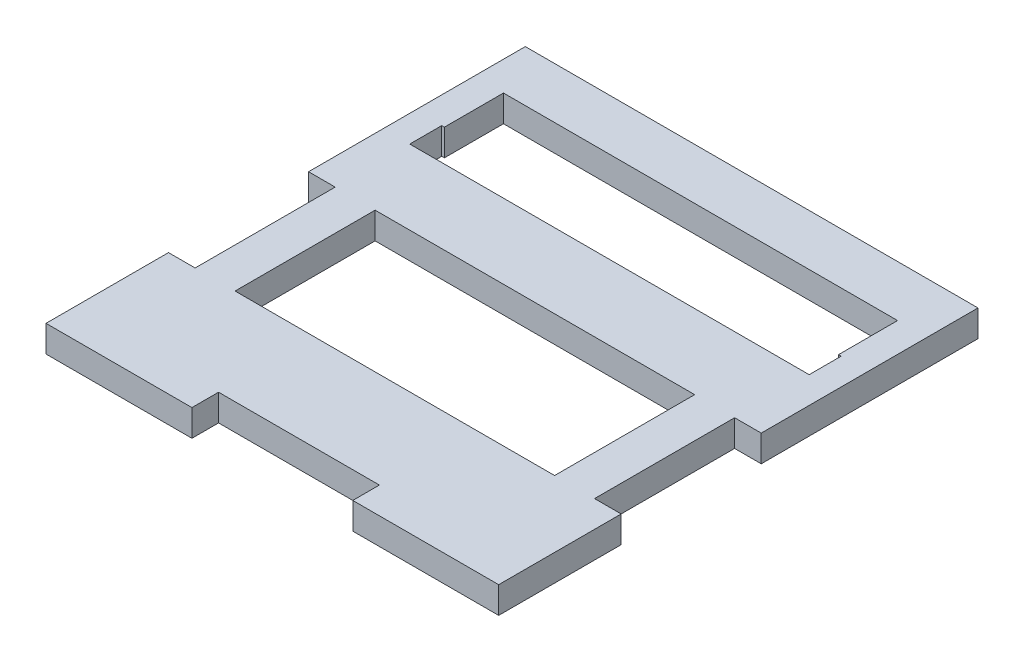
SolidWorks part; units mm, degrees
ref_plane "Front Plane" through (0, 0, 0) normal (0, 0, 1) x (1, 0, 0)
ref_plane "Top Plane" through (0, 0, 0) normal (0, 1, 0) x (1, 0, 0)
ref_plane "Right Plane" through (0, 0, 0) normal (1, 0, 0) x (0, 0, -1)
sketch "Sketch1" plane through (0, 0, 0) normal (0, 1, 0) x (1, 0, 0)
  line L1 (-42.5, -45) -> (42.5, -45)
  line L2 (-42.5, -45) -> (-42.5, 45)
  line L3 (-42.5, 45) -> (42.5, 45)
  line L4 (42.5, -45) -> (42.5, 45)
  line L5 (-42.5, -45) -> (42.5, 45) construction
  line L6 (-42.5, 45) -> (42.5, -45) construction
  point P0 (0, 0)
  dimension "D1" = 85
  dimension "D2" = 90
extrude "Boss-Extrude1" add sketch "Sketch1" along normal blind 5
sketch "Sketch2" plane through (0, 5, 0) normal (0, 1, 0) x (1, 0, 0)
  line L0 (0, -55) -> (0, 55) construction
  line L1 (-30, -22) -> (30, -22)
  line L2 (-30, -22) -> (-30, 4.3)
  line L3 (-30, 4.3) -> (30, 4.3)
  line L4 (30, -22) -> (30, 4.3)
  line L5 (-30, -22) -> (30, 4.3) construction
  line L6 (-30, 4.3) -> (30, -22) construction
  line L7 (-42.5, -45) -> (42.5, -45) construction
  line L8 (37.5, 24.3) -> (37, 24.3)
  line L9 (-37.5, 18.3) -> (37.5, 18.3)
  line L10 (-37.5, 18.3) -> (-37.5, 24.3)
  line L11 (-37, 35.4) -> (37, 35.4)
  line L12 (37.5, 18.3) -> (37.5, 24.3)
  line L13 (-37.5, 18.3) -> (37.5, 40.55) construction
  line L14 (-37, 40.4017) -> (37.5, 18.3) construction
  line L21 (-37.5, 24.3) -> (-37, 24.3)
  line L22 (-37, 35.4) -> (-37, 24.3)
  line L23 (37, 35.4) -> (37, 24.3)
  point P0 (0, -8.85)
  point P9 (0, 29.425)
  dimension "D1" = 60
  dimension "D2" = 23
  dimension "D3" = 26.3
  dimension "D4" = 14
  dimension "D5" = 22.25
  dimension "D6" = 75
  dimension "D7" = 0.5
  dimension "D8" = 11.1
  dimension "D9" = 6
extrude "Cut-Extrude2" cut sketch "Sketch2" against normal blind 7.5
sketch "Sketch4" plane through (0, 5, 0) normal (0, 1, 0) x (1, 0, 0)
  line L0 (-37.5, -22) -> (-42.5, -22)
  line L1 (-42.5, 45) -> (-42.5, -45) construction
  line L2 (-42.5, -22) -> (-42.5, 4.3)
  line L3 (-42.5, 4.3) -> (-37.5, 4.3)
  line L4 (-37.5, 4.3) -> (-37.5, -22)
  line L5 (0, -55) -> (0, 55) construction
  line L6 (37.5, 4.3) -> (37.5, -22)
  line L7 (42.5, 4.3) -> (37.5, 4.3)
  line L8 (42.5, -22) -> (42.5, 4.3)
  line L9 (37.5, -22) -> (42.5, -22)
  dimension "D1" = 5
  dimension "D2" = 26.3
extrude "Cut-Extrude3" cut sketch "Sketch4" against normal blind 7.5
sketch "Sketch5" plane through (0, 5, 0) normal (0, 1, 0) x (1, 0, 0)
  line L0 (0, -2.75) -> (0, 2.75) construction
  line L1 (-15.1, -40) -> (15.1, -40)
  line L2 (-15.1, -40) -> (-15.1, -45)
  line L3 (-15.1, -45) -> (15.1, -45)
  line L4 (15.1, -40) -> (15.1, -45)
  line L5 (-15.1, -40) -> (15.1, -45) construction
  line L6 (-15.1, -45) -> (15.1, -40) construction
  line L7 (-42.5, -45) -> (42.5, -45) construction
  point P0 (0, -42.5)
  dimension "D1" = 5
  dimension "D2" = 30.2
extrude "Cut-Extrude4" cut sketch "Sketch5" against normal blind 5
